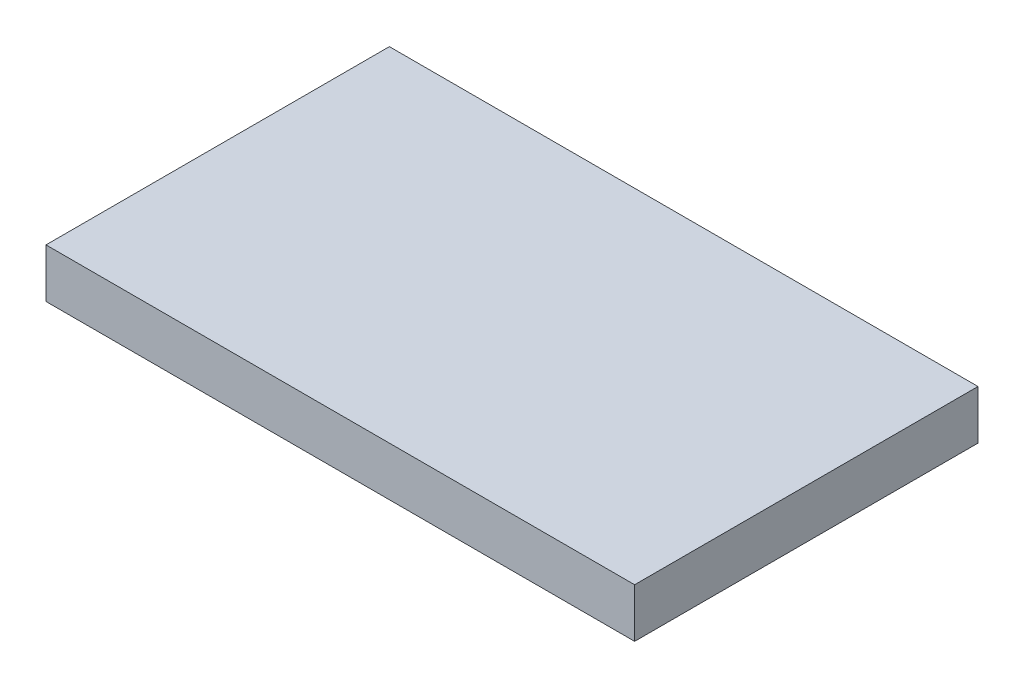
SolidWorks part; units mm, degrees
material "Balsa"
ref_plane "Front Plane" through (0, 0, 0) normal (0, 0, 1) x (1, 0, 0)
ref_plane "Top Plane" through (0, 0, 0) normal (0, 1, 0) x (1, 0, 0)
ref_plane "Right Plane" through (0, 0, 0) normal (1, 0, 0) x (0, 0, -1)
sketch "Sketch1" plane through (0, 0, 0) normal (0, 1, 0) x (1, 0, 0)
  line L1 (0, 0) -> (60, 0)
  line L2 (0, 0) -> (0, 35)
  line L3 (0, 35) -> (60, 35)
  line L4 (60, 0) -> (60, 35)
  dimension "D1" = 60
  dimension "D2" = 35
extrude "Boss-Extrude1" add sketch "Sketch1" along normal blind 5
